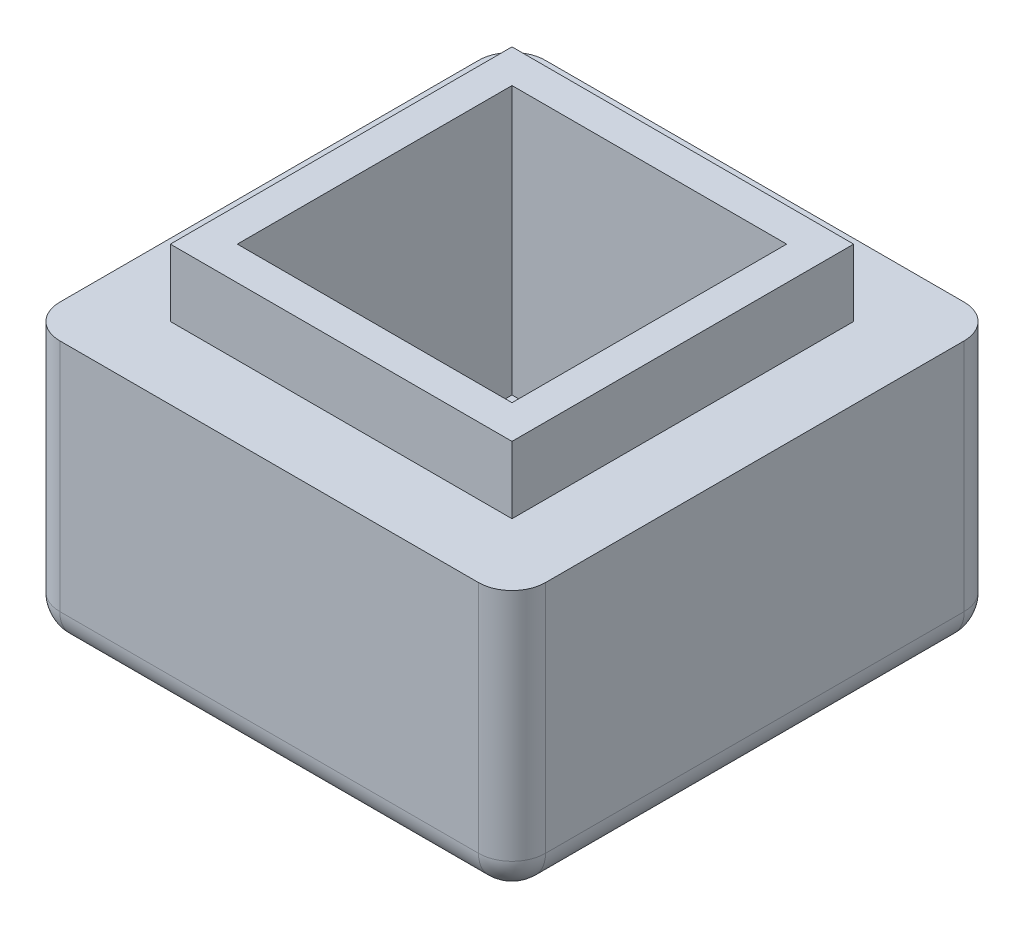
SolidWorks part; units mm, degrees
ref_plane "Front Plane" through (0, 0, 0) normal (0, 0, 1) x (1, 0, 0)
ref_plane "Top Plane" through (0, 0, 0) normal (0, 1, 0) x (1, 0, 0)
ref_plane "Right Plane" through (0, 0, 0) normal (1, 0, 0) x (0, 0, -1)
sketch "Sketch1" plane through (0, 0, 0) normal (0, 1, 0) x (1, 0, 0)
  line L1 (-3.625, -3.625) -> (3.625, -3.625)
  line L2 (-3.625, -3.625) -> (-3.625, 3.625)
  line L3 (-3.625, 3.625) -> (3.625, 3.625)
  line L4 (3.625, -3.625) -> (3.625, 3.625)
  line L5 (-3.625, -3.625) -> (3.625, 3.625) construction
  line L6 (-3.625, 3.625) -> (3.625, -3.625) construction
  point P0 (0, 0)
  dimension "D1" = 7.25
  dimension "D2" = 7.25
extrude "Boss-Extrude1" add sketch "Sketch1" along normal blind 4
sketch "Sketch3" plane through (0, 4, 0) normal (0, 1, 0) x (1, 0, 0)
  line L5 (-2.55, -2.55) -> (2.55, -2.55)
  line L11 (-2.55, -2.55) -> (-2.55, 2.55)
  line L12 (-2.55, 2.55) -> (2.55, 2.55)
  line L13 (2.55, -2.55) -> (2.55, 2.55)
  line L14 (-2.55, -2.55) -> (2.55, 2.55) construction
  line L15 (-2.55, 2.55) -> (2.55, -2.55) construction
  point P0 (0, 0)
  dimension "D1" = 5.1
  dimension "D2" = 5.1
extrude "Boss-Extrude2" add sketch "Sketch3" along normal blind 1
sketch "Sketch4" plane through (0, 5, 0) normal (0, 1, 0) x (1, 0, 0)
  line L1 (-2.05, -2.05) -> (2.05, -2.05)
  line L2 (-2.05, -2.05) -> (-2.05, 2.05)
  line L3 (-2.05, 2.05) -> (2.05, 2.05)
  line L4 (2.05, -2.05) -> (2.05, 2.05)
  line L5 (-2.05, -2.05) -> (2.05, 2.05) construction
  line L6 (-2.05, 2.05) -> (2.05, -2.05) construction
  point P0 (0, 0)
  dimension "D1" = 4.1
  dimension "D2" = 4.1
extrude "Cut-Extrude2" cut sketch "Sketch4" against normal blind 4
fillet "Fillet1" radius 0.5 8 edges at (0, 0, -3.625) (-3.625, 0, 0) (0, 0, 3.625) (3.625, 0, 0) (-3.625, 2, 3.625) (3.625, 2, -3.625) (3.625, 2, 3.625) (-3.625, 2, -3.625)
